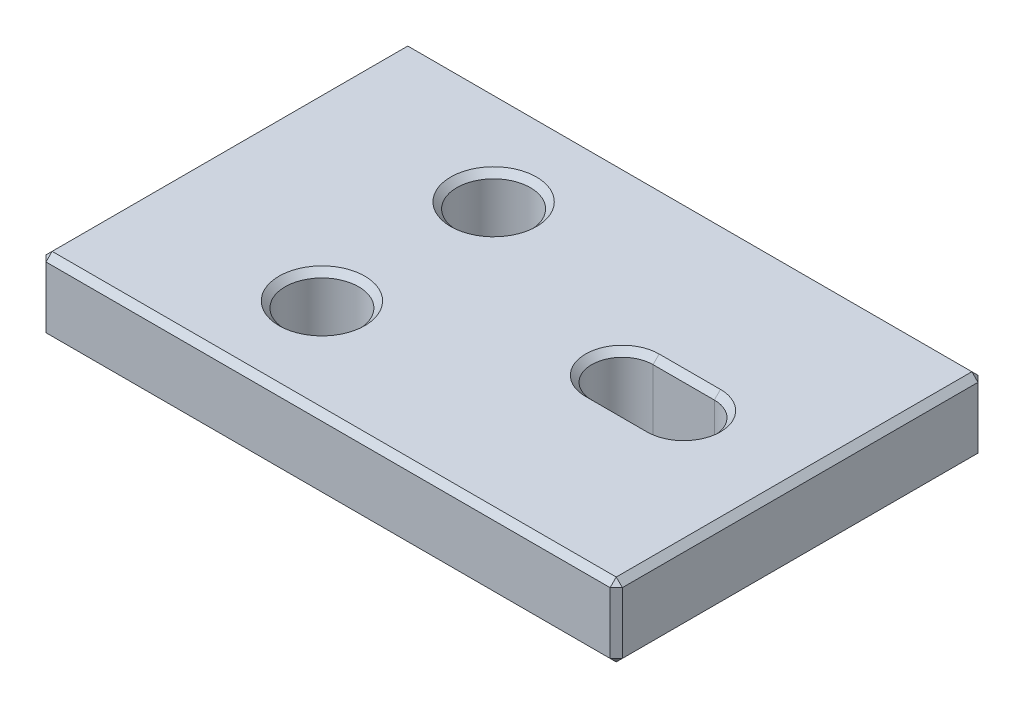
SolidWorks part; units mm, degrees
ref_plane "Alzado" through (0, 0, 0) normal (0, 0, 1) x (1, 0, 0)
ref_plane "Planta" through (0, 0, 0) normal (0, 1, 0) x (1, 0, 0)
ref_plane "Vista lateral" through (0, 0, 0) normal (1, 0, 0) x (0, 0, -1)
sketch "Croquis1" plane through (0, 0, 0) normal (0, 1, 0) x (1, 0, 0)
  line L0 (30.2717, -8.2215) -> (25.2717, -8.2215) construction
  line L1 (-7.2283, 6.7785) -> (39.7717, 6.7785)
  line L2 (-7.2283, 6.7785) -> (-7.2283, -23.2215)
  line L3 (-7.2283, -23.2215) -> (39.7717, -23.2215)
  line L4 (39.7717, 6.7785) -> (39.7717, -23.2215)
  line L5 (30.2717, -10.7215) -> (25.2717, -10.7215)
  line L6 (30.2717, -5.7215) -> (25.2717, -5.7215)
  arc A0 (30.2717, -10.7215) -> (30.2717, -5.7215) centre (30.2717, -8.2215) ccw
  arc A1 (25.2717, -5.7215) -> (25.2717, -10.7215) centre (25.2717, -8.2215) ccw
  circle A4 centre (7.7717, -1.2215) radius 3
  circle A5 centre (7.7717, -15.2215) radius 3
  point P6 (27.7717, -8.2215)
  dimension "D8" = 6
  dimension "D9" = 6
  dimension "D3" = 2.5
  dimension "D1" = 30
  dimension "D2" = 5
  dimension "D4" = 15
  dimension "D5" = 12
  dimension "D6" = 20
  dimension "D13" = 8
  dimension "D14" = 15
  dimension "D15" = 8
extrude "Saliente-Extruir1" add sketch "Croquis1" along normal blind 6
chamfer "Chaflán1" distance 0.5 angle 45 24 edges at (-7.2283, 3, -6.7785) (-7.2283, 3, 23.2215) (39.7717, 3, 23.2215) (16.2717, 0, 23.2215) (39.7717, 0, 8.2215) (-7.2283, 0, 8.2215) (16.2717, 0, -6.7785) (39.7717, 3, -6.7785) (16.2717, 6, -6.7785) (39.7717, 6, 8.2215) (16.2717, 6, 23.2215) (-7.2283, 6, 8.2215) (7.7717, 0, 18.2215) (7.7717, 0, 4.2215) (7.7717, 6, 18.2215) (7.7717, 6, 4.2215) (27.7717, 0, 10.7215) (22.7717, 0, 8.2215) (27.7717, 0, 5.7215) (32.7717, 0, 8.2215) (22.7717, 6, 8.2215) (27.7717, 6, 10.7215) (32.7717, 6, 8.2215) (27.7717, 6, 5.7215)
